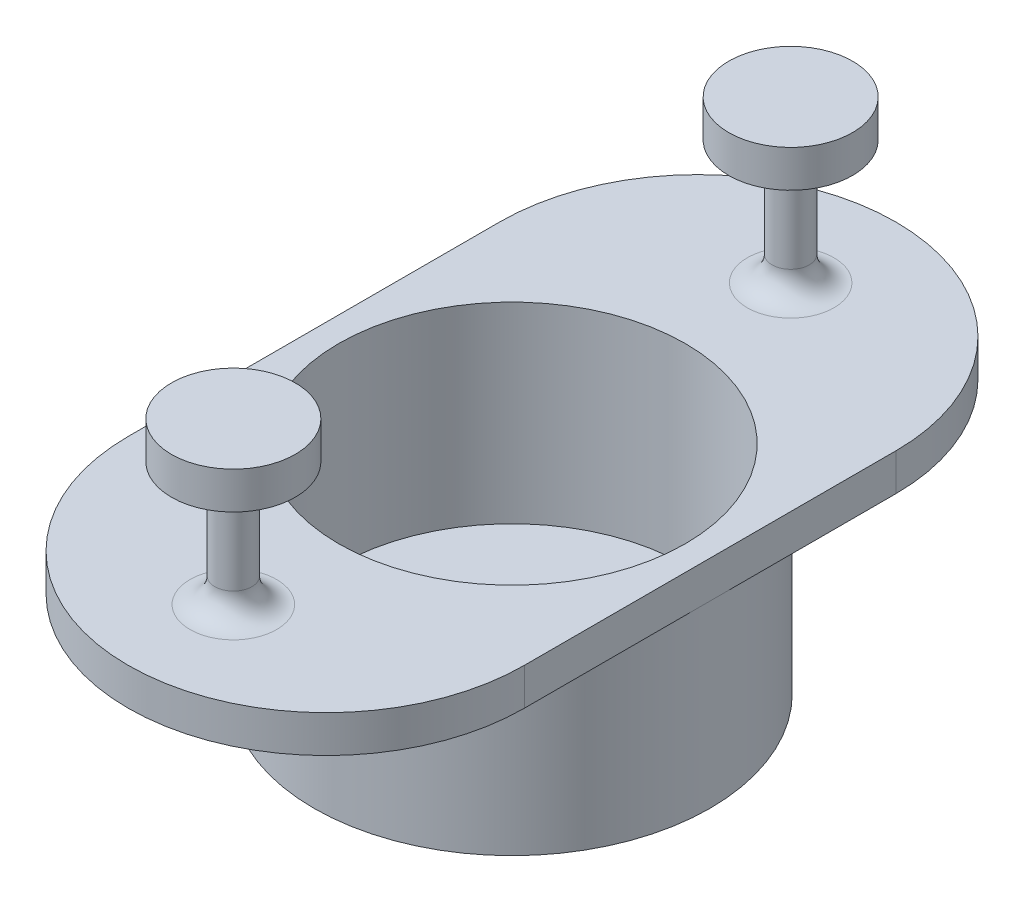
SolidWorks part; units mm, degrees
ref_plane "前视基准面" through (0, 0, 0) normal (0, 0, 1) x (1, 0, 0)
ref_plane "上视基准面" through (0, 0, 0) normal (0, 1, 0) x (1, 0, 0)
ref_plane "右视基准面" through (0, 0, 0) normal (1, 0, 0) x (0, 0, -1)
sketch "Sketch1" plane through (0, 0, 0) normal (0, 1, 0) x (1, 0, 0)
  circle A0 centre (0, 0) radius 16
  dimension "D1" = 32
extrude "Boss-Extrude1" add sketch "Sketch1" along normal blind 14.5
sketch "Sketch2" plane through (0, 14.5, 0) normal (0, 1, 0) x (1, 0, 0)
  line L0 (0, -15) -> (0, 15) construction
  line L1 (-16, -15) -> (-16, 15)
  line L2 (16, -15) -> (16, 15)
  arc A0 (-16, -15) -> (16, -15) centre (0, -15) ccw
  arc A1 (16, 15) -> (-16, 15) centre (0, 15) ccw
  circle A2 centre (0, 0) radius 16 construction
  point P2 (0, 0)
  dimension "D1" = 30
extrude "Boss-Extrude2" add sketch "Sketch2" along normal blind 3
sketch "Sketch3" plane through (0, 17.5, 0) normal (0, 1, 0) x (1, 0, 0)
  line L0 (0, -22.5) -> (0, 22.5) construction
  circle A0 centre (0, 22.5) radius 1.5
  circle A1 centre (0, -22.5) radius 1.5
  point P12 (0, 0)
  dimension "D1" = 3
  dimension "D2" = 45
extrude "Boss-Extrude3" add sketch "Sketch3" along normal blind 10
sketch "Sketch4" plane through (0, 17.5, 0) normal (0, 1, 0) x (1, 0, 0)
  circle A0 centre (0, 0) radius 14
  circle A1 centre (0, 0) radius 16 construction
  dimension "D1" = 2
extrude "Cut-Extrude1" cut sketch "Sketch4" against normal offset from surface (15.5 mm away) 2 up to face at (0, 0, 16)
sketch "Sketch5" plane through (0, 2, 0) normal (0, 1, 0) x (1, 0, 0)
  circle A0 centre (7.5, 0) radius 3 construction
  circle A1 centre (7.5, 0) radius 1.5
  circle A2 centre (-7.5, 0) radius 1.5
  point P13 (0, 0)
  dimension "D1" = 7.5
  dimension "D2" = 3
  dimension "D3" = 6
  dimension "D4" = 2
extrude "Cut-Extrude2" cut sketch "Sketch5" against normal through all
sketch "Sketch6" plane through (0, 0, 0) normal (0, -1, 0) x (1, 0, 0)
  circle A0 centre (0, 0) radius 4.3467
sketch "Sketch7" plane through (0, 27.5, 0) normal (0, 1, 0) x (1, 0, 0)
  circle A0 centre (0, 22.5) radius 5
  circle A1 centre (0, -22.5) radius 5
  dimension "D1" = 10
extrude "Boss-Extrude4" add sketch "Sketch7" along normal blind 3
fillet "Fillet1" radius 2 4 edges at (0, 27.5, -21) (0, 27.5, 24) (0, 17.5, 24) (0, 17.5, -21)
